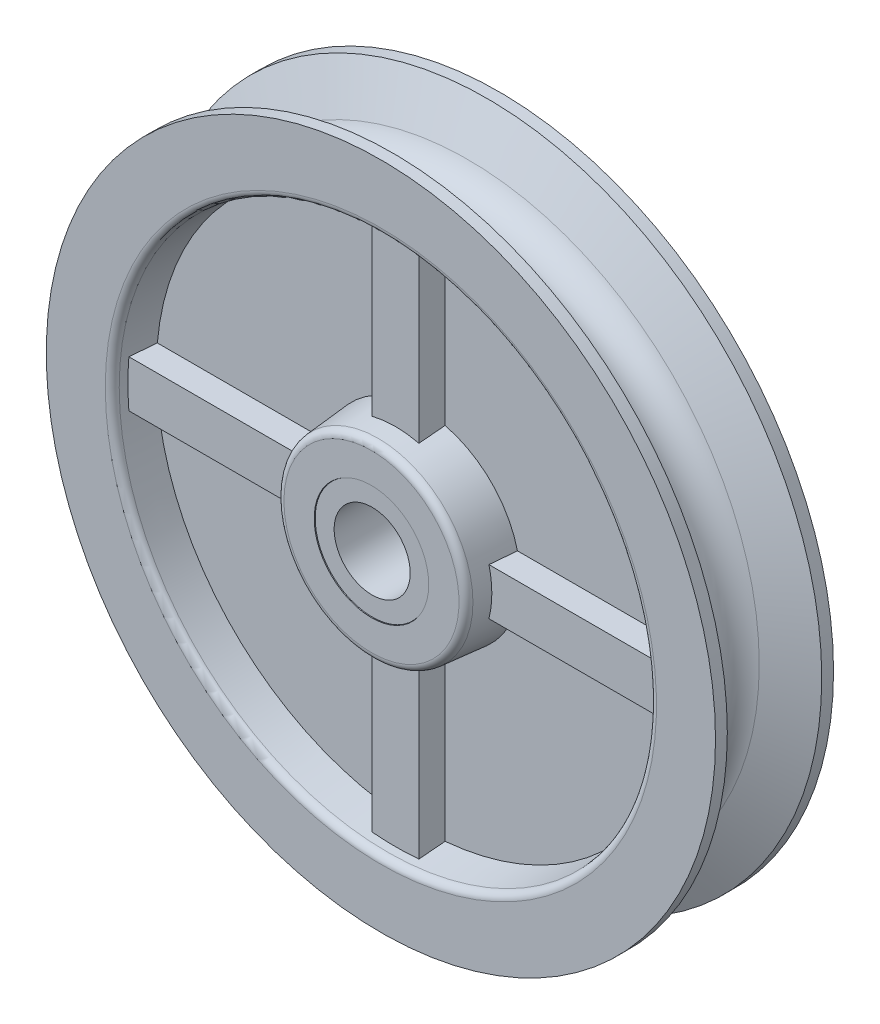
SolidWorks part; units mm, degrees
ref_plane "Front" through (0, 0, 0) normal (0, 0, 1) x (1, 0, 0)
ref_plane "Top" through (0, 0, 0) normal (0, 1, 0) x (1, 0, 0)
ref_plane "Right" through (0, 0, 0) normal (1, 0, 0) x (0, 0, -1)
sketch "Sketch1" plane through (0, 0, 0) normal (1, 0, 0) x (0, 0, -1)
  line L0 (4.9276, 34.925) -> (6.1595, 34.925)
  line L1 (-4.9276, 34.925) -> (-6.1595, 34.925)
  line L2 (-4.9276, 34.925) -> (-2.8912, 30.4379)
  line L3 (7.1438, 9.9219) -> (7.1438, 5.9531)
  line L4 (7.0676, 3.9688) -> (-7.0675, 3.9687)
  line L5 (-7.1437, 5.9531) -> (-7.1437, 9.9219)
  line L6 (4.9276, 34.925) -> (2.8912, 30.4379)
  line L8 (-7.1437, 0) -> (7.1437, 0) construction
  line L10 (6.1595, 34.925) -> (6.1595, 28.067)
  line L12 (-7.1437, 5.9531) -> (-7.0675, 5.9531)
  line L13 (-7.0675, 5.9531) -> (-7.0675, 3.9687)
  line L14 (0, 28.575) -> (0, -28.575) construction
  line L15 (7.0676, 5.9531) -> (7.1438, 5.9531)
  line L16 (7.0676, 5.9531) -> (7.0676, 3.9688)
  line L17 (-6.1595, 34.925) -> (-6.1595, -34.925) construction
  line L18 (-6.1595, 28.067) -> (-1.905, 28.067)
  line L19 (-1.905, 28.067) -> (-1.905, 9.9219)
  line L20 (-1.905, 9.9219) -> (-7.1437, 9.9219)
  line L21 (-6.1595, 28.067) -> (-6.1595, 34.925)
  line L22 (6.1595, 28.067) -> (1.905, 28.067)
  line L23 (1.905, 28.067) -> (1.905, 9.9219)
  line L24 (1.905, 9.9219) -> (7.1438, 9.9219)
  arc A0 (-2.8912, 30.4379) -> (2.8912, 30.4379) centre (0, 31.75) ccw
  circle A1 centre (0, 31.75) radius 3.175 construction
  circle A2 centre (0, 0) radius 3.9688 construction
  circle A3 centre (0, 0) radius 5.9531 construction
  circle A4 centre (0, 0) radius 9.9219 construction
  circle A5 centre (0, -31.75) radius 3.175 construction
  point P28 (-6.1595, 0)
  dimension "Rope Dia" = 6.35
  dimension "Shaft Dia" = 7.9375
  dimension "D1" = 11.9062
  dimension "D3" = 19.8438
  dimension "Wd" = 14.2875
  dimension "D8" = 1.2319
  dimension "D9" = 0.0762
  dimension "Groove Dia" = 57.15
  dimension "OD" = 69.85
  dimension "D2" = 3.81
  dimension "w Wd" = 12.319
  dimension "D4" = 0.508
revolve "Revolve1" add sketch "Sketch1" angle 360 about L8
sketch "Sketch2" plane through (0, 0, 0) normal (0, 0, 1) x (1, 0, 0)
  circle A0 centre (0, 0) radius 5.9531 construction
  circle A1 centre (0, 0) radius 5.9531
extrude "Cut-Extrude-Thin1" cut sketch "Sketch2" against normal through all and the other way through all thin
draft "Draft1" type of draft neutral plane draft angle 5 faces to draft 2 face at (9.9219, 0, 7.1437) face at (28.067, 0, 1.905) neutral plane through (0, 28.067, 6.1595) neutral plane normal (0, 0, 1) parameters "D1"=5
draft "Draft2" type of draft neutral plane draft angle 15 faces to draft 2 face at (9.9219, 0, -1.905) face at (28.067, 0, -6.1595) neutral plane through (0, 34.925, -6.1595) neutral plane normal (0, 0, -1) parameters "D1"=15
fillet "Fillet1" radius 0.762 4 edges at (28.067, 0, 6.1595) (28.067, 0, -6.1595) (-9.8358, 0, 7.1437) (9.6581, 0, -7.1438)
sketch "Sketch4" plane through (0, 0, 0) normal (0, 0, 1) x (1, 0, 0)
  line L0 (0, 28.067) -> (0, 5.9531)
extrude "Extrude-Thin1" add sketch "Sketch4" along normal offset from surface 1.524 and the other way offset from surface (4.6355 mm away) 1.524 thin up to face at (-28.7652, 0, 6.1595) other way up to face at (28.6517, 0, -6.1595) thin type mid plane wall 4.8895
pattern_circular "CirPattern1" count 4 over 360 about axis through (0, 0, 0) along (0, 0, 1) of "Extrude-Thin1"
equation "\"D1@Sketch1\" = \"Shaft Dia@Sketch1\" * 1.5"
equation "\"D3@Sketch1\" = \"Shaft Dia@Sketch1\" * 2.5"
equation "\"D5@Extrude-Thin1\" = \"OD@Sketch1\" * .07"
